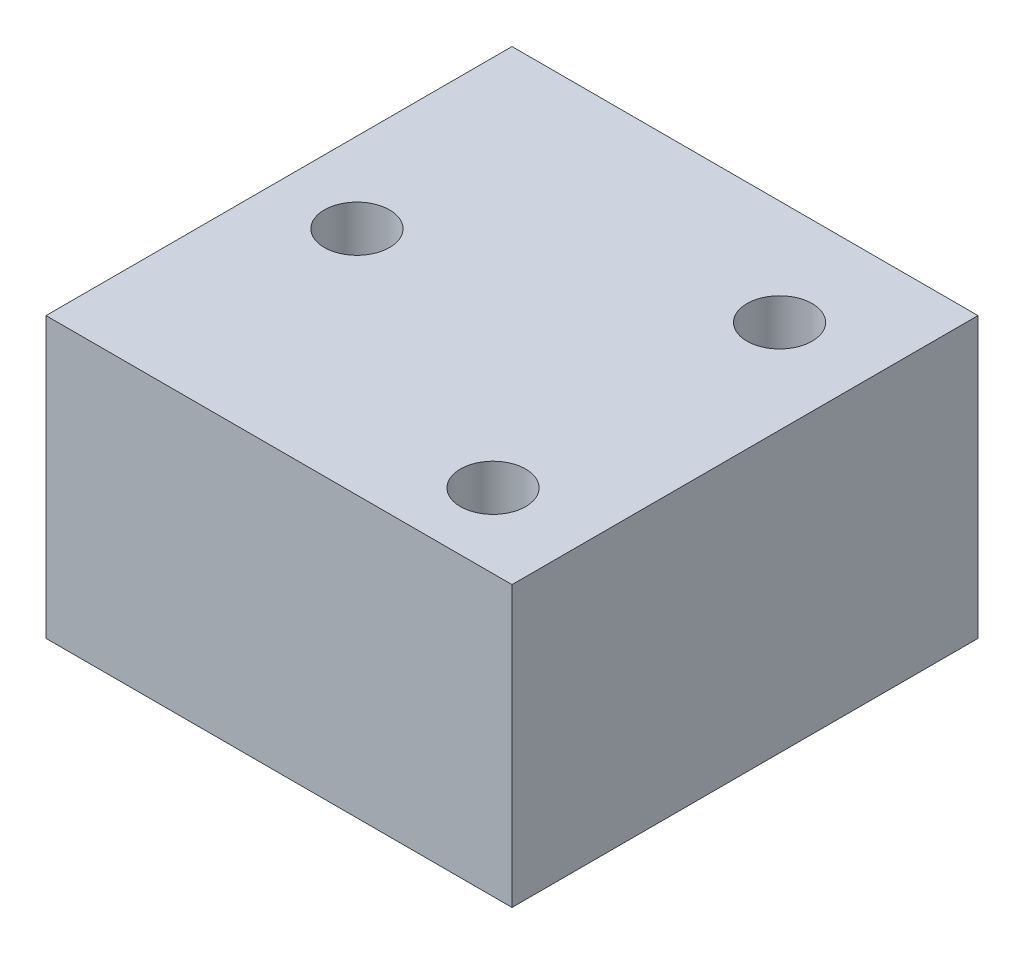
SolidWorks part; units mm, degrees
ref_plane "Front Plane" through (0, 0, 0) normal (0, 0, 1) x (1, 0, 0)
ref_plane "Top Plane" through (0, 0, 0) normal (0, 1, 0) x (1, 0, 0)
ref_plane "Right Plane" through (0, 0, 0) normal (1, 0, 0) x (0, 0, -1)
sketch "Sketch1" plane through (0, 0, 0) normal (0, 1, 0) x (1, 0, 0)
  line L1 (0, 0) -> (50, 0)
  line L2 (0, 0) -> (0, 50)
  line L3 (0, 50) -> (50, 50)
  line L4 (50, 0) -> (50, 50)
  dimension "D1" = 50
  dimension "D2" = 50
extrude "Boss-Extrude1" add sketch "Sketch1" along normal blind 30
sketch "Sketch2" plane through (0, 30, 0) normal (0, 1, 0) x (1, 0, 0)
  circle A0 centre (39.9864, 38.7229) radius 3.5
  circle A1 centre (39.9864, 7.978) radius 3.5
  circle A2 centre (8.6098, 24.7543) radius 3.5
  dimension "D1" = 7
extrude "Cut-Extrude1" cut sketch "Sketch2" against normal blind 10
